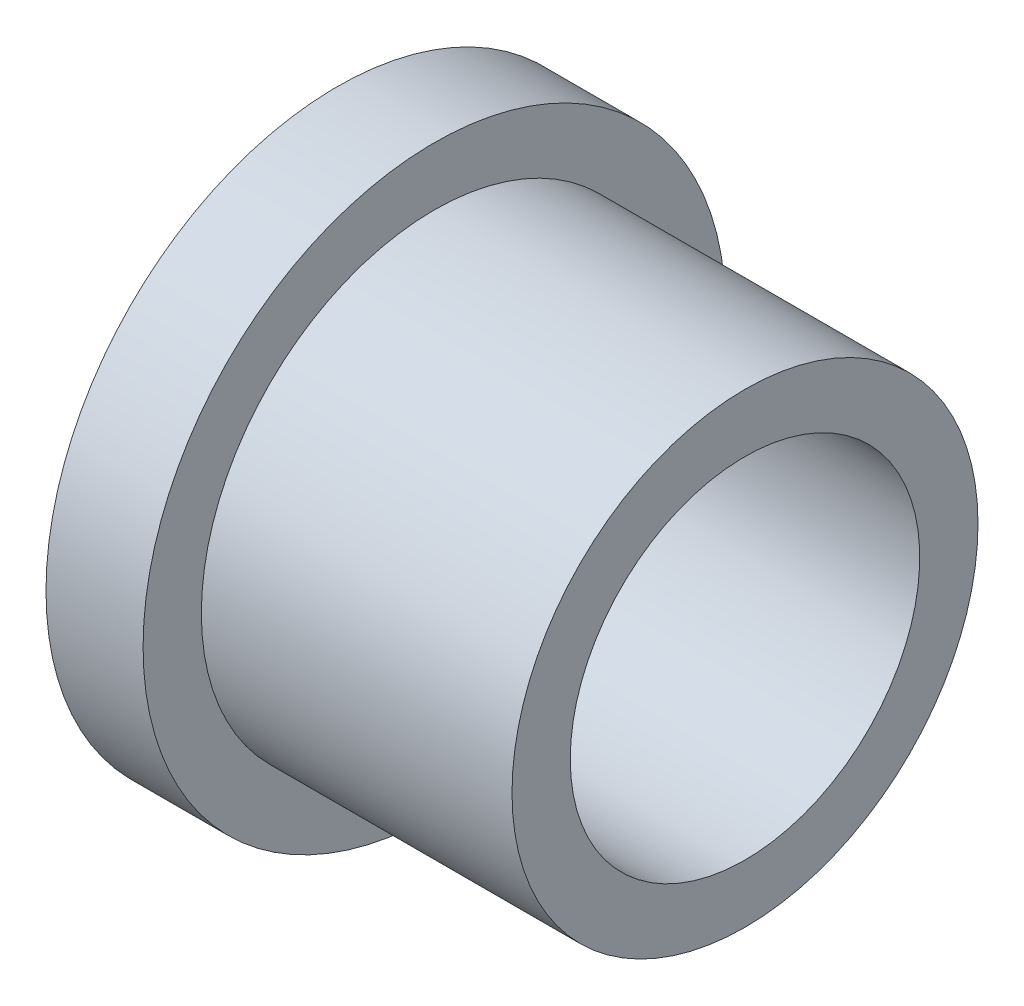
SolidWorks part; units mm, degrees
ref_plane "Front Plane" through (0, 0, 0) normal (0, 0, 1) x (1, 0, 0)
ref_plane "Top Plane" through (0, 0, 0) normal (0, 1, 0) x (1, 0, 0)
ref_plane "Right Plane" through (0, 0, 0) normal (1, 0, 0) x (0, 0, -1)
sketch "Sketch1" plane through (0, 0, 0) normal (0, 0, 1) x (1, 0, 0)
  line L0 (0, 9) -> (0, 15)
  line L1 (0, 15) -> (5, 15)
  line L2 (5, 15) -> (5, 12)
  line L3 (5, 12) -> (21, 12)
  line L4 (21, 12) -> (21, 9)
  line L5 (21, 9) -> (0, 9)
  line L6 (0, 0) -> (20.5854, 0)
revolve "Revolve1" add sketch "Sketch1" angle 360 about L6
